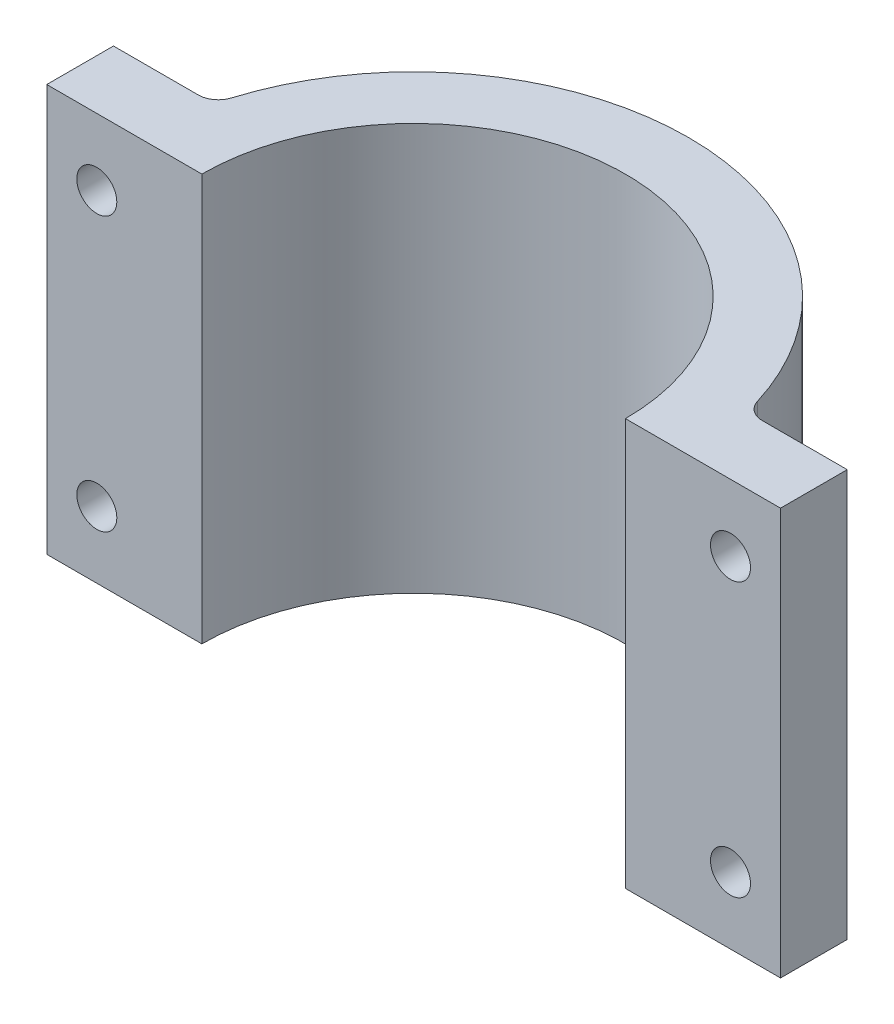
SolidWorks part; units mm, degrees
ref_plane "Front Plane" through (0, 0, 0) normal (0, 0, 1) x (1, 0, 0)
ref_plane "Top Plane" through (0, 0, 0) normal (0, 1, 0) x (1, 0, 0)
ref_plane "Right Plane" through (0, 0, 0) normal (1, 0, 0) x (0, 0, -1)
sketch "Sketch1" plane through (0, 0, 0) normal (0, 1, 0) x (1, 0, 0)
  line L0 (0, 0) -> (-40, 0) construction
  line L1 (-40, 0) -> (-40, -20)
  line L2 (0, 0) -> (40, 0) construction
  line L3 (40, 0) -> (40, -20) construction
  line L4 (-40, 0) -> (-40, -41.75) construction
  line L5 (-40, -51.75) -> (0, -51.75) construction
  line L6 (0, -51.75) -> (0, -20) construction
  line L7 (40, -20) -> (40, -41.75) construction
  line L8 (40, -51.75) -> (31.75, -51.75)
  line L9 (-40, -51.75) -> (-31.75, -51.75)
  line L10 (-40, -51.75) -> (-55, -51.75)
  line L11 (-55, -51.75) -> (-55, -41.75)
  line L12 (-55, -41.75) -> (-40, -41.75)
  line L13 (40, -51.75) -> (55, -51.75)
  line L14 (55, -51.75) -> (55, -41.75)
  line L15 (55, -41.75) -> (40, -41.75)
  arc A0 (31.75, -51.75) -> (-31.75, -51.75) centre (0, -51.75) ccw construction
  arc A1 (31.75, -51.75) -> (-31.75, -51.75) centre (0, -51.75) ccw
  arc A2 (40, -41.75) -> (-40, -41.75) centre (0, -51.75) ccw
  dimension "D1" = 20
  dimension "D2" = 40
  dimension "D3" = 40
  dimension "D4" = 31.75
  dimension "D5" = 31.75
  dimension "D6" = 15
  dimension "D7" = 10
  dimension "D8" = 31.75
extrude "Boss-Extrude1" add sketch "Sketch1" along normal blind 61 contours A1 L8 L13 L14 L15 L7 L3 L2 L0 L1 L4 L12 L11 L10 L9
sketch "Sketch2" plane through (0, 0, 41.75) normal (0, 0, -1) x (-1, 0, 0)
  line L0 (0, 0) -> (0, 61) construction
  line L2 (-55, 61) -> (-55, 0) construction
  line L3 (-55, 61) -> (-40, 61) construction
  line L4 (-55, 0) -> (-40, 0) construction
  line L5 (40, 61) -> (-40, 61) construction
  circle A0 centre (-47.5, 51) radius 3
  circle A1 centre (-47.5, 10) radius 3
  circle A4 centre (47.5, 10) radius 3
  circle A5 centre (47.5, 51) radius 3
  dimension "D2" = 6
  dimension "D1" = 7.5
  dimension "D3" = 10
  dimension "D4" = 10
extrude "Cut-Extrude1" cut sketch "Sketch2" against normal through all and the other way through all
fillet "Fillet1" radius 3 2 edges at (-40, 30.5, 41.75) (40, 30.5, 41.75)
